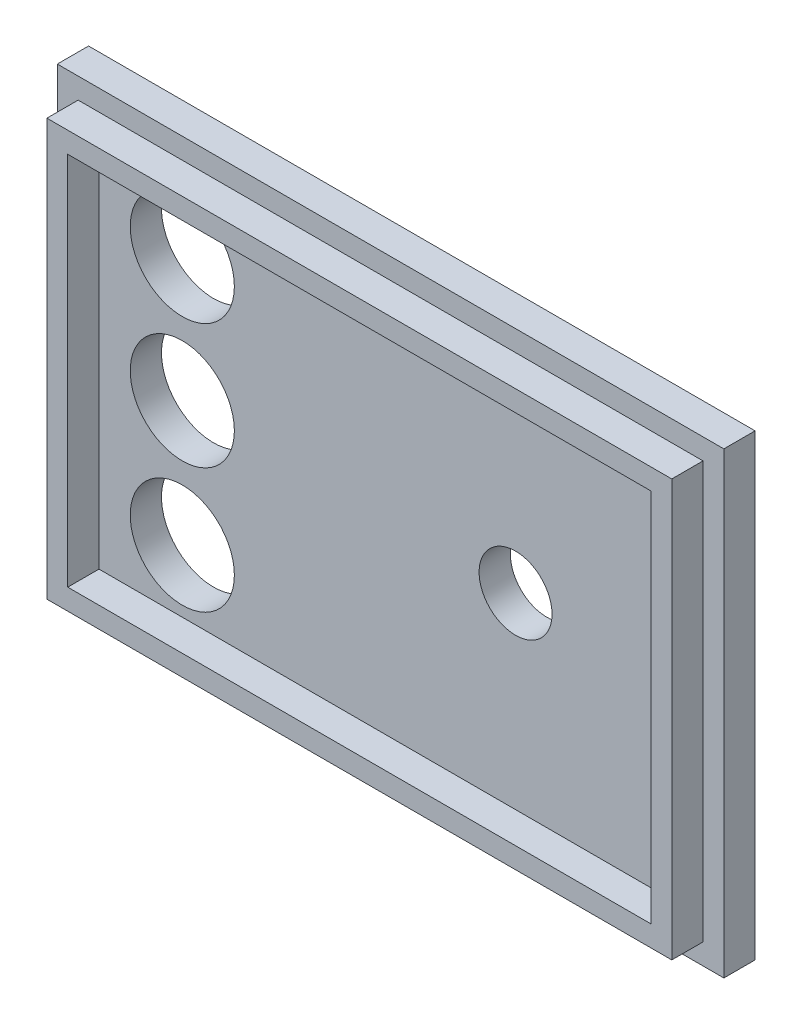
SolidWorks part; units mm, degrees
ref_plane "Alzado" through (0, 0, 0) normal (0, 0, 1) x (1, 0, 0)
ref_plane "Planta" through (0, 0, 0) normal (0, 1, 0) x (1, 0, 0)
ref_plane "Vista lateral" through (0, 0, 0) normal (1, 0, 0) x (0, 0, -1)
sketch "Croquis1" plane through (0, 0, 0) normal (0, 0, 1) x (1, 0, 0)
  line L1 (0, 0) -> (-64, 0)
  line L2 (0, 0) -> (0, 44)
  line L3 (0, 44) -> (-64, 44)
  line L4 (-64, 0) -> (-64, 44)
  circle A0 centre (-52, 34) radius 5
  circle A2 centre (-52, 10) radius 5
  circle A3 centre (-20, 22) radius 3.5
  circle A4 centre (-52, 22) radius 5
  dimension "D3" = 10
  dimension "D4" = 10
  dimension "D5" = 10
  dimension "D6" = 10
  dimension "D7" = 10
  dimension "D8" = 7
  dimension "D9" = 12
  dimension "D10" = 12
  dimension "D11" = 20
  dimension "D12" = 22
  dimension "D13" = 12
  dimension "D14" = 12
  dimension "D1" = 64
  dimension "D2" = 44
extrude "Saliente-Extruir1" add sketch "Croquis1" along normal blind 3
sketch "Croquis3" plane through (0, 0, 3) normal (0, 0, 1) x (1, 0, 0)
  line L0 (0, 0) -> (0, 44) construction
  line L1 (-62, 42) -> (-2, 42)
  line L2 (-62, 42) -> (-62, 2)
  line L3 (-62, 2) -> (-2, 2)
  line L4 (-2, 42) -> (-2, 2)
  line L5 (-60, 40) -> (-4, 40)
  line L6 (-60, 40) -> (-60, 4)
  line L7 (-60, 4) -> (-4, 4)
  line L8 (-4, 40) -> (-4, 4)
  line L9 (0, 44) -> (-64, 44) construction
  dimension "D1" = 60
  dimension "D2" = 40
  dimension "D3" = 56
  dimension "D4" = 36
  dimension "D5" = 2
  dimension "D6" = 2
  dimension "D7" = 2
  dimension "D8" = 2
extrude "Saliente-Extruir2" add sketch "Croquis3" along normal blind 3
